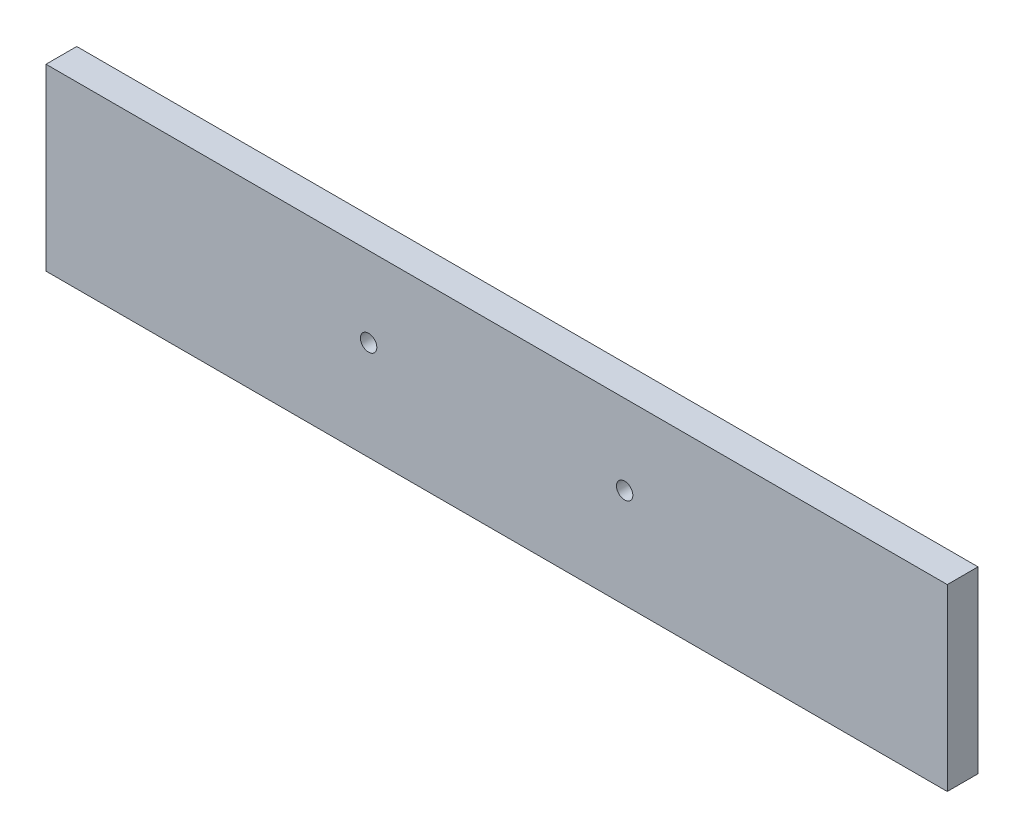
SolidWorks part; units mm, degrees
material "Oak"
ref_plane "Front Plane" through (0, 0, 0) normal (0, 0, 1) x (1, 0, 0)
ref_plane "Top Plane" through (0, 0, 0) normal (0, 1, 0) x (1, 0, 0)
ref_plane "Right Plane" through (0, 0, 0) normal (1, 0, 0) x (0, 0, -1)
sketch "Sketch1" plane through (0, 0, 0) normal (0, 0, 1) x (1, 0, 0)
  line L0 (0, -3.3) -> (0, 3.3) construction
  line L1 (-88, -17.5) -> (88, -17.5)
  line L2 (-88, -17.5) -> (-88, 17.5)
  line L3 (-88, 17.5) -> (88, 17.5)
  line L4 (88, -17.5) -> (88, 17.5)
  line L5 (-88, -17.5) -> (88, 17.5) construction
  line L6 (-88, 17.5) -> (88, -17.5) construction
  circle A0 centre (-25, 1.9) radius 1.6
  circle A1 centre (25, 1.9) radius 1.6
  point P0 (0, 0)
  point P12 (-25, 3.5)
  dimension "D3" = 25
  dimension "D4" = 3.2
  dimension "D5" = 14
  dimension "D1" = 35
  dimension "D2" = 176
extrude "Boss-Extrude1" add sketch "Sketch1" along normal blind 6
